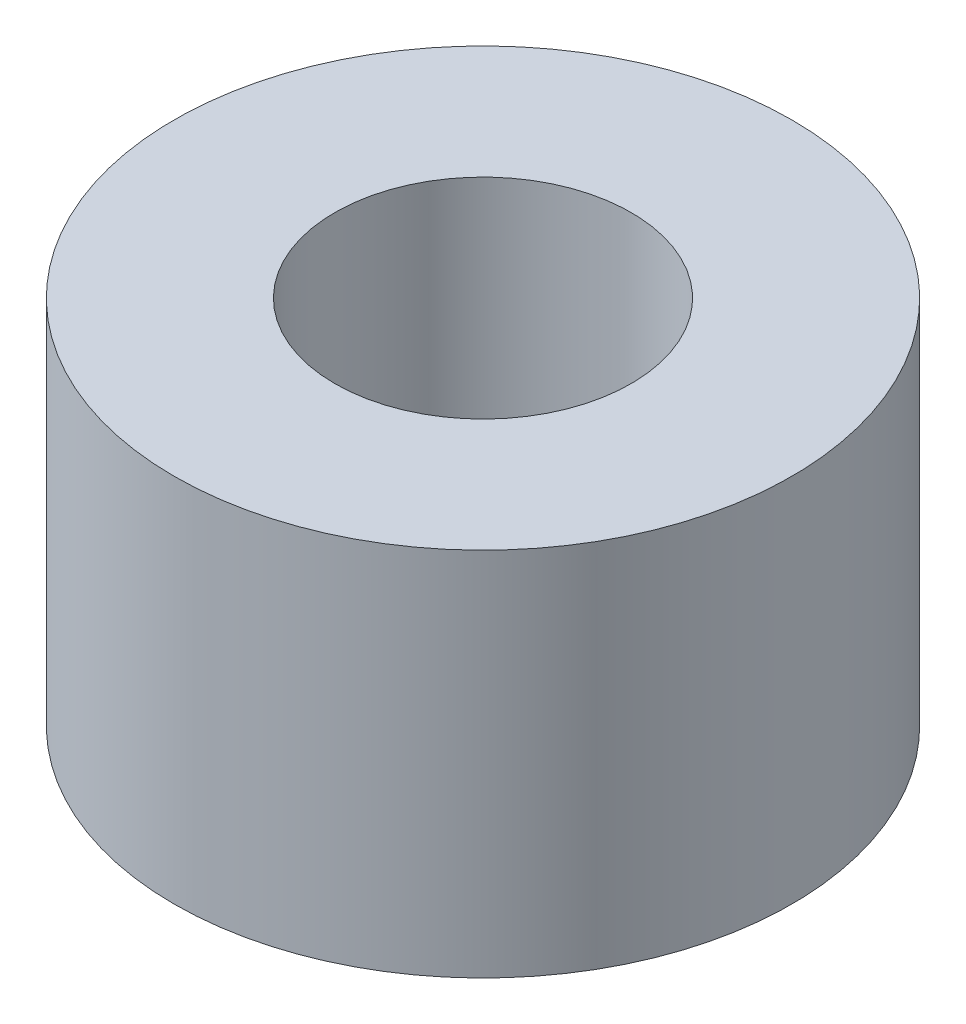
SolidWorks part; units mm, degrees
material "AISI 316 Stainless Steel Sheet (SS)"
ref_plane "Front Plane" through (0, 0, 0) normal (0, 0, 1) x (1, 0, 0)
ref_plane "Top Plane" through (0, 0, 0) normal (0, 1, 0) x (1, 0, 0)
ref_plane "Right Plane" through (0, 0, 0) normal (1, 0, 0) x (0, 0, -1)
sketch "Sketch1" plane through (0, 0, 0) normal (1, 0, 0) x (0, 0, -1)
  line L0 (-60, 25.1724) -> (-60, -109.8276)
  line L1 (-60, -109.8276) -> (0, -109.8276)
  line L2 (0, 120) -> (0, -180.6897) construction
  line L3 (-125, 25.1724) -> (-125, -124.8276)
  line L4 (-125, -124.8276) -> (0, -124.8276)
  line L5 (-125, 25.1724) -> (-60, 25.1724)
  line L6 (0, -109.8276) -> (0, -124.8276)
  dimension "D1" = 60
  dimension "D2" = 125
  dimension "D3" = 15
  dimension "D4" = 150
revolve "Revolve1" add sketch "Sketch1" angle 360 about L2
